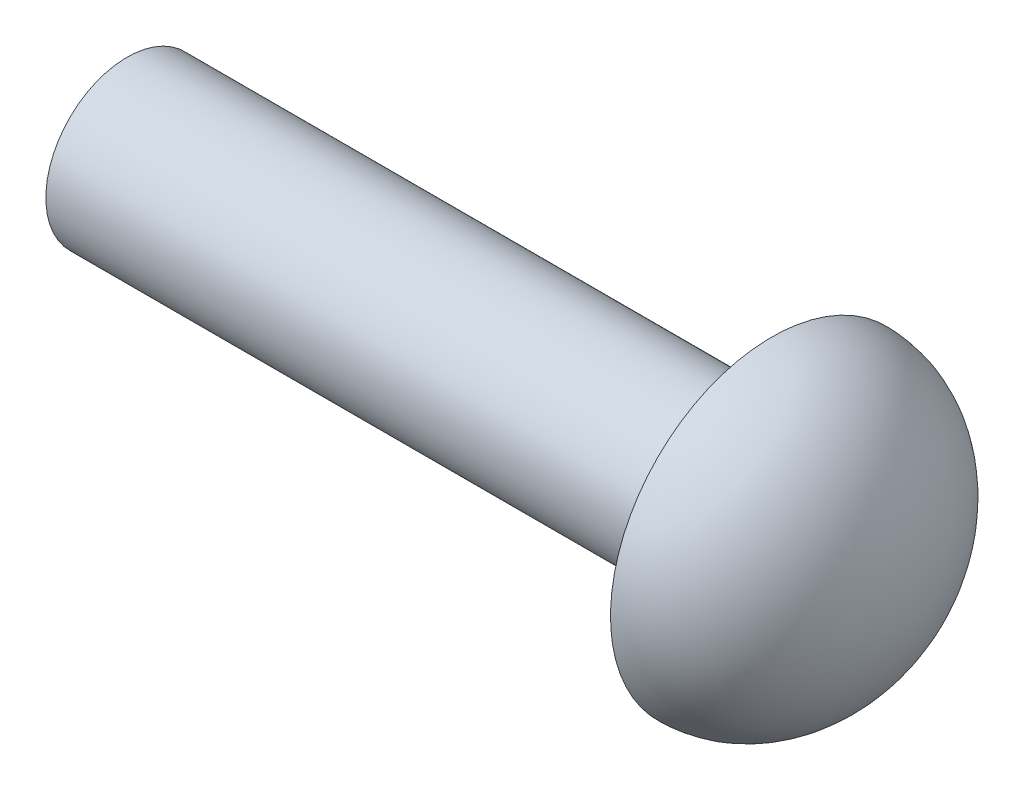
SolidWorks part; units mm, degrees
ref_plane "Front Plane" through (0, 0, 0) normal (0, 0, 1) x (1, 0, 0)
ref_plane "Top Plane" through (0, 0, 0) normal (0, 1, 0) x (1, 0, 0)
ref_plane "Right Plane" through (0, 0, 0) normal (1, 0, 0) x (0, 0, -1)
sketch "Sketch1" plane through (0, 0, 0) normal (0, 0, 1) x (1, 0, 0)
  line L0 (0, 0) -> (0, -1.2603)
  line L1 (0, -1.2603) -> (10, -1.2603)
  line L2 (10, -1.2603) -> (10, -2.5)
  line L5 (12, 0) -> (0, 0)
  ellipse E0 centre (10, 0) end of major axis (10, 2.5) minor radius 2 (10, -2.5) -> (12, 0) ccw
  point P6 (0, 0)
  point P9 (10.7133, 0)
  dimension "D1" = 10
  dimension "D2" = 2
  dimension "D3" = 2.5
revolve "Revolve1" add sketch "Sketch1" angle 360 about L5
